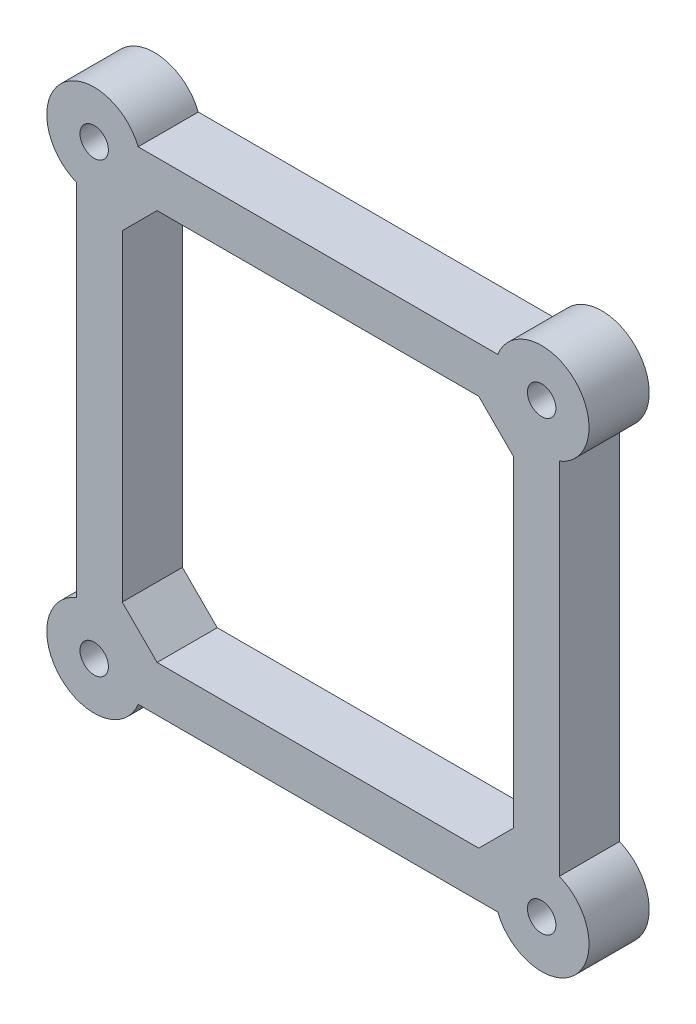
SolidWorks part; units mm, degrees
ref_plane "Plan de face" through (0, 0, 0) normal (0, 0, 1) x (1, 0, 0)
ref_plane "Plan de dessus" through (0, 0, 0) normal (0, 1, 0) x (1, 0, 0)
ref_plane "Plan de droite" through (0, 0, 0) normal (1, 0, 0) x (0, 0, -1)
sketch "Esquisse28" plane through (0, 0, 0) normal (0, 0, 1) x (1, 0, 0)
  line L0 (-18.97, -25.4754) -> (-25.4754, -18.97)
  line L1 (18.97, -25.4754) -> (-18.97, -25.4754)
  line L4 (25.4754, -18.97) -> (18.97, -25.4754)
  line L5 (25.4754, 18.97) -> (25.4754, -18.97)
  line L8 (18.97, 25.4754) -> (25.4754, 18.97)
  line L9 (-18.97, 25.4754) -> (18.97, 25.4754)
  line L10 (-25.4754, 18.97) -> (-18.97, 25.4754)
  line L11 (-25.4754, -18.97) -> (-25.4754, 18.97)
  line L16 (-16.97, -20.6455) -> (-20.6455, -16.97)
  line L17 (16.97, -20.6455) -> (-16.97, -20.6455)
  line L18 (20.6455, -16.97) -> (16.97, -20.6455)
  line L19 (20.6455, 16.97) -> (20.6455, -16.97)
  line L20 (16.97, 20.6455) -> (20.6455, 16.97)
  line L21 (-16.97, 20.6455) -> (16.97, 20.6455)
  line L22 (-20.6455, 16.97) -> (-16.97, 20.6455)
  line L23 (-20.6455, -16.97) -> (-20.6455, 16.97)
  point P0 (20.6455, -28.9519)
  point P1 (0, -20.6455)
  point P2 (0, -25.4754)
  point P3 (25.4754, 0)
  point P6 (0, 0)
  point P24 (20.6455, 0)
  dimension "D1" = 33.94
  dimension "D2" = 5.198
  dimension "D3" = 135
  dimension "D4" = 135
  dimension "D5" = 37.94
  dimension "D6" = 9.2
  dimension "D7" = 135
  dimension "D8" = 135
extrude "Boss.-Extru.2" add sketch "Esquisse28" along normal blind 6.35
sketch "Esquisse29" plane through (0, 0, 0) normal (0, 0, 1) x (1, 0, 0)
  line L0 (-46.0327, -46.0327) -> (46.0327, 46.0327) construction
  line L1 (-59.4617, 0) -> (59.4617, 0) construction
  circle A0 centre (23.6083, 23.6083) radius 5
  point P4 (0, 0)
  point P8 (0, 0)
  point P9 (32.5174, 23.4283)
  point P10 (25.891, 25.891)
  dimension "D2" = 10
  dimension "D1" = 45
extrude "Boss.-Extru.3" add sketch "Esquisse29" along normal up to surface (6.35 mm away) up to face at (0, 0, 6.35)
mirror "Symétrie1" about plane through (0, 0, 0) normal (1, 0, 0) of "Boss.-Extru.3"
mirror "Symétrie2" about plane through (0, 0, 0) normal (0, 1, 0) of "Symétrie1", "Boss.-Extru.3"
sketch "Esquisse30" plane through (0, 0, 6.35) normal (0, 0, 1) x (1, 0, 0)
  circle A0 centre (-23.6083, 23.6083) radius 1.5
  circle A1 centre (23.6083, 23.6083) radius 1.5
  circle A2 centre (23.6083, -23.6083) radius 1.5
  circle A3 centre (-23.6083, -23.6083) radius 1.5
  arc A4 (-25.4754, -18.97) -> (-18.97, -25.4754) centre (-23.6083, -23.6083) ccw construction
  arc A5 (-18.97, 25.4754) -> (-25.4754, 18.97) centre (-23.6083, 23.6083) ccw construction
  arc A6 (25.4754, 18.97) -> (18.97, 25.4754) centre (23.6083, 23.6083) ccw construction
  arc A7 (18.97, -25.4754) -> (25.4754, -18.97) centre (23.6083, -23.6083) ccw construction
  dimension "D1" = 3
extrude "Enlèv. mat.-Extru.1" cut sketch "Esquisse30" against normal through all
